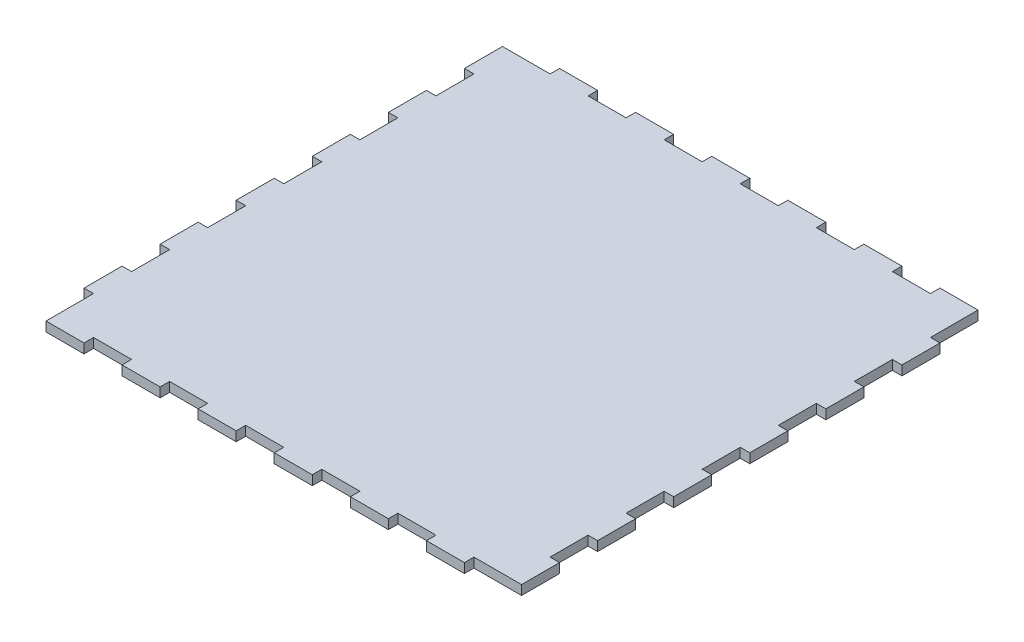
SolidWorks part; units mm, degrees
ref_plane "Front Plane" through (0, 0, 0) normal (0, 0, 1) x (1, 0, 0)
ref_plane "Top Plane" through (0, 0, 0) normal (0, 1, 0) x (1, 0, 0)
ref_plane "Right Plane" through (0, 0, 0) normal (1, 0, 0) x (0, 0, -1)
sketch "Sketch1" plane through (0, 0, 0) normal (0, 1, 0) x (1, 0, 0)
  line L0 (-65.2925, -101.6) -> (-39.8925, -101.6)
  line L1 (-97.0425, 152.4) -> (-97.0425, 127)
  line L2 (-97.0425, 203.2) -> (-97.0425, 177.8)
  line L3 (-90.6925, -107.95) -> (-65.2925, -107.95)
  line L4 (188.7075, 209.55) -> (214.1075, 209.55)
  line L5 (-90.6925, 177.8) -> (-90.6925, 152.4)
  line L6 (-97.0425, 203.2) -> (-65.2925, 203.2)
  line L7 (214.1075, 209.55) -> (214.1075, 177.8)
  line L8 (-65.2925, 209.55) -> (-65.2925, 203.2)
  line L9 (-39.8925, 209.55) -> (-39.8925, 203.2)
  line L10 (-14.4925, 209.55) -> (-14.4925, 203.2)
  line L11 (36.3075, 209.55) -> (36.3075, 203.2)
  line L12 (61.7075, 209.55) -> (61.7075, 203.2)
  line L13 (87.1075, 209.55) -> (87.1075, 203.2)
  line L14 (112.5075, 209.55) -> (112.5075, 203.2)
  line L15 (10.9075, 209.55) -> (10.9075, 203.2)
  line L16 (137.9075, 209.55) -> (137.9075, 203.2)
  line L17 (163.3075, 209.55) -> (163.3075, 203.2)
  line L18 (188.7075, 209.55) -> (188.7075, 203.2)
  line L19 (-97.0425, -76.2) -> (-90.6925, -76.2)
  line L20 (-97.0425, -50.8) -> (-90.6925, -50.8)
  line L21 (-97.0425, -25.4) -> (-90.6925, -25.4)
  line L22 (-97.0425, 0) -> (-90.6925, 0)
  line L23 (-97.0425, 25.4) -> (-90.6925, 25.4)
  line L24 (-97.0425, 50.8) -> (-90.6925, 50.8)
  line L25 (-97.0425, 76.2) -> (-90.6925, 76.2)
  line L26 (-97.0425, 101.6) -> (-90.6925, 101.6)
  line L27 (-97.0425, 127) -> (-90.6925, 127)
  line L28 (-97.0425, 152.4) -> (-90.6925, 152.4)
  line L29 (-97.0425, 177.8) -> (-90.6925, 177.8)
  line L30 (-39.8925, -107.95) -> (-14.4925, -107.95)
  line L31 (10.9075, -107.95) -> (36.3075, -107.95)
  line L32 (61.7075, -107.95) -> (87.1075, -107.95)
  line L33 (112.5075, -107.95) -> (137.9075, -107.95)
  line L34 (163.3075, -107.95) -> (188.7075, -107.95)
  line L35 (220.4575, -76.2) -> (220.4575, -101.6)
  line L36 (220.4575, -25.4) -> (220.4575, -50.8)
  line L37 (220.4575, 25.4) -> (220.4575, 0)
  line L38 (220.4575, 76.2) -> (220.4575, 50.8)
  line L39 (220.4575, 127) -> (220.4575, 101.6)
  line L40 (220.4575, 177.8) -> (220.4575, 152.4)
  line L41 (137.9075, 209.55) -> (163.3075, 209.55)
  line L42 (87.1075, 209.55) -> (112.5075, 209.55)
  line L43 (36.3075, 209.55) -> (61.7075, 209.55)
  line L44 (-14.4925, 209.55) -> (10.9075, 209.55)
  line L45 (-65.2925, 209.55) -> (-39.8925, 209.55)
  line L46 (-97.0425, 101.6) -> (-97.0425, 76.2)
  line L47 (-97.0425, 50.8) -> (-97.0425, 25.4)
  line L48 (-97.0425, 0) -> (-97.0425, -25.4)
  line L49 (-97.0425, -50.8) -> (-97.0425, -76.2)
  line L50 (-39.8925, 203.2) -> (-14.4925, 203.2)
  line L51 (10.9075, 203.2) -> (36.3075, 203.2)
  line L52 (61.7075, 203.2) -> (87.1075, 203.2)
  line L53 (112.5075, 203.2) -> (137.9075, 203.2)
  line L54 (163.3075, 203.2) -> (188.7075, 203.2)
  line L66 (-90.6925, -76.2) -> (-90.6925, -107.95)
  line L67 (-90.6925, 127) -> (-90.6925, 101.6)
  line L68 (-90.6925, 76.2) -> (-90.6925, 50.8)
  line L69 (-90.6925, 25.4) -> (-90.6925, 0)
  line L70 (-90.6925, -25.4) -> (-90.6925, -50.8)
  line L71 (-14.4925, -101.6) -> (10.9075, -101.6)
  line L72 (36.3075, -101.6) -> (61.7075, -101.6)
  line L73 (87.1075, -101.6) -> (112.5075, -101.6)
  line L74 (137.9075, -101.6) -> (163.3075, -101.6)
  line L75 (188.7075, -101.6) -> (220.4575, -101.6)
  line L76 (214.1075, -50.8) -> (214.1075, -76.2)
  line L77 (214.1075, 0) -> (214.1075, -25.4)
  line L78 (214.1075, 50.8) -> (214.1075, 25.4)
  line L79 (214.1075, 76.2) -> (220.4575, 76.2)
  line L80 (214.1075, 101.6) -> (214.1075, 76.2)
  line L81 (214.1075, 152.4) -> (214.1075, 127)
  line L82 (214.1075, 177.8) -> (220.4575, 177.8)
  line L83 (214.1075, 152.4) -> (220.4575, 152.4)
  line L84 (214.1075, 127) -> (220.4575, 127)
  line L85 (214.1075, 101.6) -> (220.4575, 101.6)
  line L86 (214.1075, 50.8) -> (220.4575, 50.8)
  line L87 (214.1075, 25.4) -> (220.4575, 25.4)
  line L88 (214.1075, 0) -> (220.4575, 0)
  line L89 (214.1075, -25.4) -> (220.4575, -25.4)
  line L90 (214.1075, -50.8) -> (220.4575, -50.8)
  line L91 (214.1075, -76.2) -> (220.4575, -76.2)
  line L92 (188.7075, -101.6) -> (188.7075, -107.95)
  line L93 (163.3075, -101.6) -> (163.3075, -107.95)
  line L94 (137.9075, -101.6) -> (137.9075, -107.95)
  line L95 (112.5075, -101.6) -> (112.5075, -107.95)
  line L96 (87.1075, -101.6) -> (87.1075, -107.95)
  line L97 (61.7075, -101.6) -> (61.7075, -107.95)
  line L98 (36.3075, -101.6) -> (36.3075, -107.95)
  line L99 (10.9075, -101.6) -> (10.9075, -107.95)
  line L100 (-14.4925, -101.6) -> (-14.4925, -107.95)
  line L101 (-39.8925, -101.6) -> (-39.8925, -107.95)
  line L102 (-65.2925, -101.6) -> (-65.2925, -107.95)
  dimension "D3" = 6.35
  dimension "D4" = 6.35
  dimension "D7" = 25.4
  dimension "D8" = 50.8
  dimension "D9" = 76.2
  dimension "D10" = 101.6
  dimension "D11" = 127
  dimension "D12" = 152.4
  dimension "D13" = 177.8
  dimension "D14" = 203.2
  dimension "D15" = 228.6
  dimension "D16" = 254
  dimension "D17" = 279.4
  dimension "D18" = 25.4
  dimension "D19" = 50.8
  dimension "D20" = 76.2
  dimension "D21" = 101.6
  dimension "D22" = 127
  dimension "D23" = 152.4
  dimension "D24" = 177.8
  dimension "D25" = 203.2
  dimension "D26" = 228.6
  dimension "D27" = 254
  dimension "D28" = 279.4
  dimension "D29" = 304.8
extrude "Boss-Extrude1" add sketch "Sketch1" along normal blind 6.35
sketch "Sketch2" plane through (0, 6.35, 0) normal (0, 1, 0) x (1, 0, 0)
  line L0 (-97.0425, 203.2) -> (220.4575, -101.6) construction
  line L1 (-90.6925, -107.95) -> (214.1075, 209.55) construction
  line L2 (61.7075, 50.8) -> (220.4575, 50.8) construction
  line L3 (214.1075, 50.8) -> (220.4575, 50.8) construction
  line L4 (61.7075, 50.8) -> (-97.0425, 50.8) construction
  line L5 (61.7075, 50.8) -> (61.7075, 209.55) construction
  line L6 (61.7075, 50.8) -> (61.7075, -107.95) construction
  line L8 (-33.5425, -57.15) -> (156.9575, -57.15)
  line L9 (-33.5425, -57.15) -> (-33.5425, 158.75)
  line L10 (-33.5425, 158.75) -> (156.9575, 158.75)
  line L11 (156.9575, -57.15) -> (156.9575, 158.75)
  line L12 (-33.5425, -57.15) -> (156.9575, 158.75) construction
  line L13 (-33.5425, 158.75) -> (156.9575, -57.15) construction
  point P8 (61.7075, 50.8)
  dimension "D1" = 215.9
  dimension "D2" = 190.5
